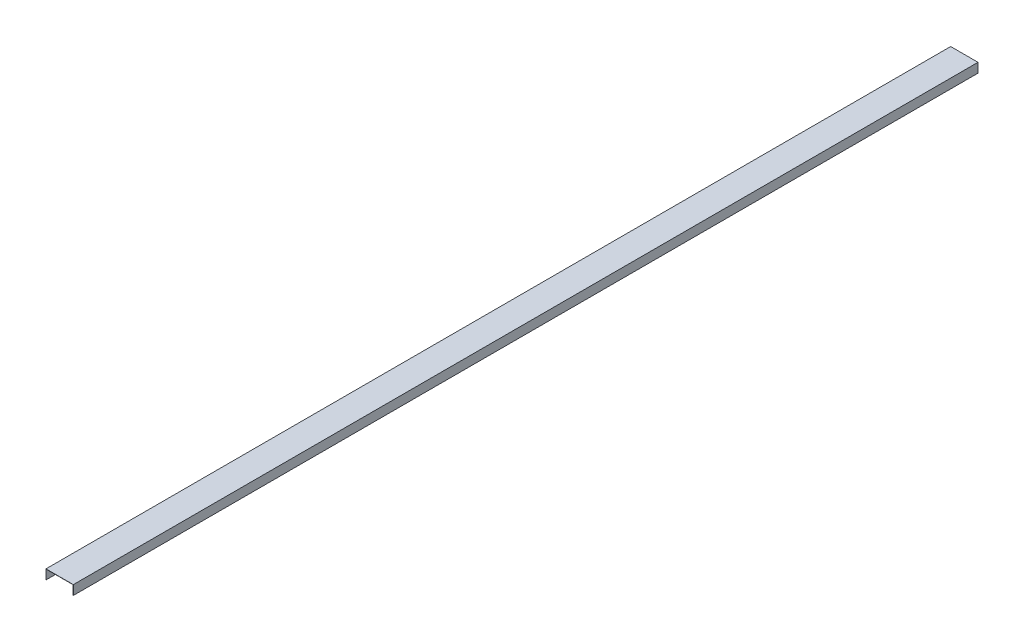
SolidWorks part; units mm, degrees
ref_plane "Front Plane" through (0, 0, 0) normal (0, 0, 1) x (1, 0, 0)
ref_plane "Top Plane" through (0, 0, 0) normal (0, 1, 0) x (1, 0, 0)
ref_plane "Right Plane" through (0, 0, 0) normal (1, 0, 0) x (0, 0, -1)
sketch "Sketch1" plane through (0, 0, 0) normal (0, 1, 0) x (1, 0, 0)
  line L1 (-46.0375, 1524) -> (46.0375, 1524)
  line L2 (-46.0375, 1524) -> (-46.0375, -1524)
  line L3 (-46.0375, -1524) -> (46.0375, -1524)
  line L4 (46.0375, 1524) -> (46.0375, -1524)
  line L5 (-46.0375, 1524) -> (46.0375, -1524) construction
  line L6 (-46.0375, -1524) -> (46.0375, 1524) construction
  point P0 (0, 0)
  dimension "D1" = 3048
  dimension "D2" = 92.075
extrude "Boss-Extrude1" add sketch "Sketch1" along normal blind 31.75
sketch "Sketch2" plane through (0, 0, 0) normal (0, 1, 0) x (1, 0, 0)
  line L0 (-46.0375, -1524) -> (46.0375, -1524) construction
  line L1 (-45.2755, 1524) -> (45.2755, 1524)
  line L2 (-45.2755, 1524) -> (-45.2755, -1524)
  line L3 (-45.2755, -1524) -> (45.2755, -1524)
  line L4 (45.2755, 1524) -> (45.2755, -1524)
  line L5 (-45.2755, 1524) -> (45.2755, -1524) construction
  line L6 (-45.2755, -1524) -> (45.2755, 1524) construction
  line L7 (46.0375, -1524) -> (46.0375, 1524) construction
  point P0 (0, 0)
  dimension "D1" = 0.762
extrude "Cut-Extrude1" cut sketch "Sketch2" along normal blind 30.988
